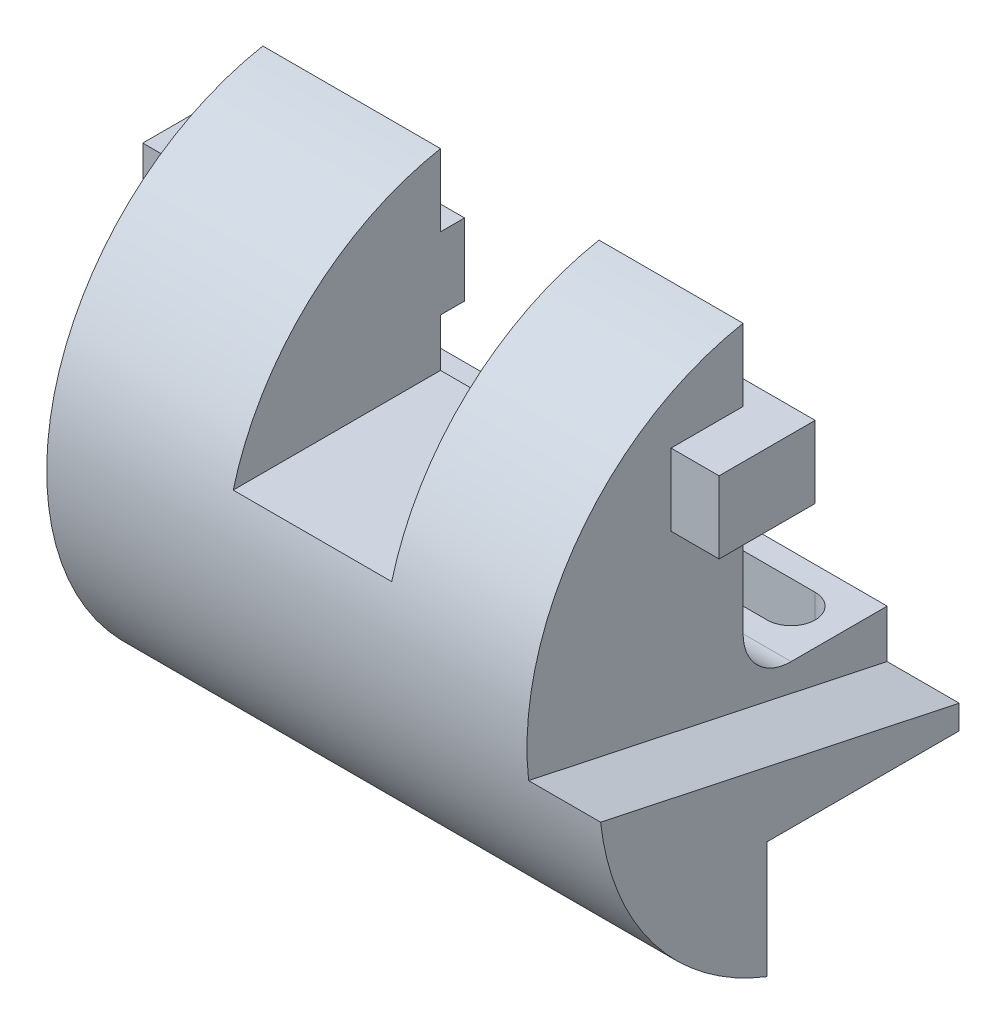
SolidWorks part; units mm, degrees
material "1060 Alloy"
ref_plane "Front Plane" through (0, 0, 0) normal (0, 0, 1) x (1, 0, 0)
ref_plane "Top Plane" through (0, 0, 0) normal (0, 1, 0) x (1, 0, 0)
ref_plane "Right Plane" through (0, 0, 0) normal (1, 0, 0) x (0, 0, -1)
sketch "Sketch1" plane through (0, 0, 0) normal (1, 0, 0) x (0, 0, -1)
  line L0 (0, -79.524) -> (0, 79.524) construction
  line L1 (0, 79.524) -> (0, 0) construction
  line L2 (-86.1633, 0) -> (86.1633, 0) construction
  line L3 (-10, 54.0833) -> (-10, -1.9167)
  line L4 (0, -11.9167) -> (20, -11.9167)
  line L5 (20, -11.9167) -> (20, -26.9167)
  line L6 (20, -26.9167) -> (-20, -26.9167)
  line L7 (-20, -26.9167) -> (-20, -51.2348)
  line L8 (20, -11.9167) -> (20, -1.9167) construction
  arc A0 (-10, 54.0833) -> (-20, -51.2348) centre (0, 0) ccw
  arc A1 (0, -11.9167) -> (-10, -1.9167) centre (0, -1.9167) cw
  point P4 (0, 0)
  point P9 (0, 0)
  point P17 (-10, -11.9167)
  dimension "D1" = 110
  dimension "D7" = 10
  dimension "D2" = 10
  dimension "D3" = 20
  dimension "D4" = 66
  dimension "D5" = 20
  dimension "D6" = 15
extrude "Boss-Extrude1" add sketch "Sketch1" along normal blind 115
sketch "Sketch2" plane through (115, 0, 0) normal (1, 0, 0) x (0, 0, -1)
  line L0 (20, -21.9167) -> (-54.6667, -6.0458)
  line L1 (20, -26.9167) -> (20, -11.9167) construction
  line L2 (-10, 54.0833) -> (-10, -1.9167)
  line L3 (0, -11.9167) -> (20, -11.9167)
  line L4 (20, -11.9167) -> (20, -21.9167)
  arc A0 (-10, 54.0833) -> (-20, -51.2348) centre (0, 0) ccw construction
  arc A1 (-54.6667, -6.0458) -> (-10, 54.0833) centre (-5.7414, 4.265) cw
  arc A2 (-10, -1.9167) -> (0, -11.9167) centre (0, -1.9167) ccw
  dimension "D3" = 50
  dimension "D1" = 5
  dimension "D2" = 78
extrude "Cut-Extrude3" cut sketch "Sketch2" against normal blind 15
sketch "Sketch4" plane through (0, -11.9167, 0) normal (0, 1, 0) x (1, 0, 0)
  line L0 (10, 10) -> (90, 10) construction
  line L1 (10, 15) -> (90, 15)
  line L2 (10, 5) -> (90, 5)
  line L3 (100, 20) -> (100, 0) construction
  line L6 (100, 20) -> (0, 20) construction
  arc A0 (10, 15) -> (10, 5) centre (10, 10) ccw
  arc A1 (90, 5) -> (90, 15) centre (90, 10) ccw
  point P2 (50, 10)
  point P9 (-13.1488, 69.8457)
  dimension "D1" = 80
  dimension "D2" = 10
  dimension "D3" = 10
  dimension "D4" = 10
extrude "Cut-Extrude4" cut sketch "Sketch4" against normal blind 67
sketch "Sketch5" plane through (0, 0, 10) normal (0, 0, -1) x (-1, 0, 0)
  line L0 (-100, 54.0833) -> (0, 54.0833) construction
  line L1 (-70, 54.0833) -> (-37, 54.0833)
  line L2 (-70, 54.0833) -> (-70, 14.0833)
  line L3 (-70, 14.0833) -> (-37, 14.0833)
  line L4 (-37, 54.0833) -> (-37, 14.0833)
  point P6 (-68.25, 48.9898)
  point P7 (-28.9941, 48.9898)
  point P10 (-114.4441, 65.1622)
  dimension "D1" = 33
  dimension "D2" = 30
  dimension "D3" = 40
extrude "Cut-Extrude5" cut sketch "Sketch5" against normal blind 67
sketch "Sketch6" plane through (0, 0, 10) normal (0, 0, -1) x (-1, 0, 0)
  line L0 (-37, 14.0833) -> (-37, 54.0833) construction
  line L1 (-37, 39.0833) -> (3, 39.0833)
  line L2 (-37, 39.0833) -> (-37, 24.0833)
  line L3 (-37, 24.0833) -> (3, 24.0833)
  line L4 (3, 39.0833) -> (3, 24.0833)
  point P7 (-37, 31.5833)
  dimension "D1" = 40
  dimension "D2" = 10
  dimension "D3" = 15
extrude "Boss-Extrude2" add sketch "Sketch6" along normal blind 5
sketch "Sketch7" plane through (0, 0, 0) normal (-1, 0, 0) x (0, 0, 1)
  line L1 (10, 39.0833) -> (25, 39.0833)
  line L2 (10, 39.0833) -> (10, 24.0833)
  line L3 (10, 24.0833) -> (25, 24.0833)
  line L4 (25, 39.0833) -> (25, 24.0833)
  dimension "D1" = 15
  dimension "D2" = 15
extrude "Boss-Extrude4" add sketch "Sketch7" along normal blind 10
sketch "Sketch8" plane through (0, 0, 10) normal (0, 0, -1) x (-1, 0, 0)
  line L1 (3, 39.0833) -> (10, 39.0833)
  line L2 (3, 39.0833) -> (3, 24.0833)
  line L3 (3, 24.0833) -> (10, 24.0833)
  line L4 (10, 39.0833) -> (10, 24.0833)
extrude "Boss-Extrude5" add sketch "Sketch8" along normal blind 5
sketch "Sketch9" plane through (0, 0, 10) normal (0, 0, -1) x (-1, 0, 0)
  line L0 (-70, 54.0833) -> (-70, 14.0833) construction
  line L1 (-70, 39.0833) -> (-110, 39.0833)
  line L2 (-70, 39.0833) -> (-70, 24.0833)
  line L3 (-70, 24.0833) -> (-110, 24.0833)
  line L4 (-110, 39.0833) -> (-110, 24.0833)
  dimension "D1" = 40
  dimension "D2" = 10
  dimension "D3" = 15
extrude "Boss-Extrude6" add sketch "Sketch9" along normal blind 5 and the other way blind 15
